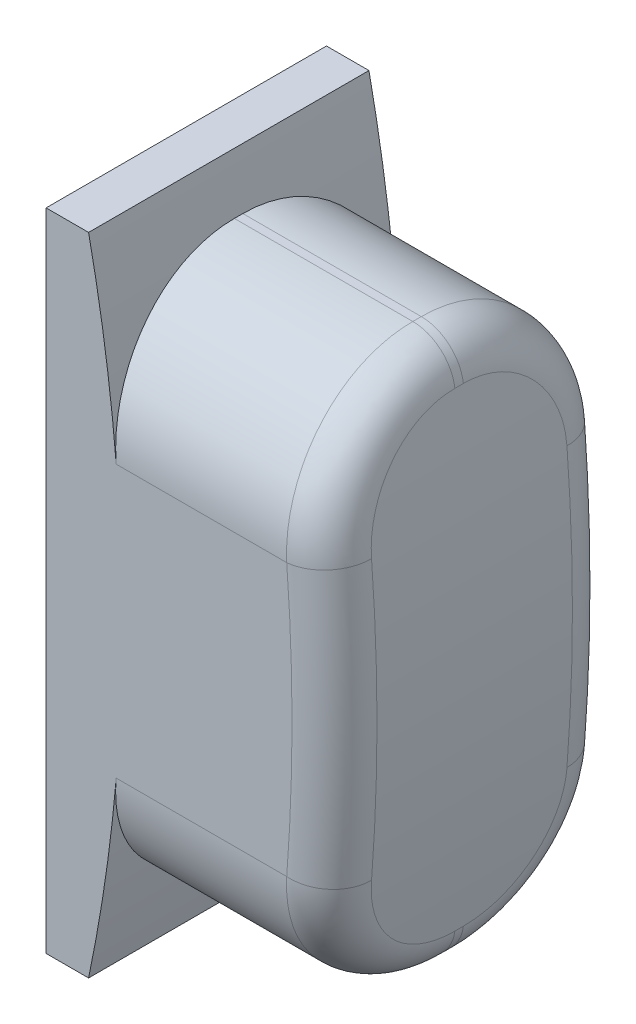
SolidWorks part; units mm, degrees
ref_plane "Ebene vorne" through (0, 0, 0) normal (0, 0, 1) x (1, 0, 0)
ref_plane "Ebene oben" through (0, 0, 0) normal (0, 1, 0) x (1, 0, 0)
ref_plane "Ebene rechts" through (0, 0, 0) normal (1, 0, 0) x (0, 0, -1)
sketch "Sketch1" plane through (0, 0, 0) normal (0, 0, 1) x (1, 0, 0)
  line L0 (0, 0) -> (21, 0) construction
  line L1 (18.2211, 3.2) -> (20.7548, 3.2)
  line L2 (18.2211, -3.2) -> (20.7548, -3.2)
  line L3 (17.6055, 3.8) -> (18.1055, 3.8)
  line L4 (17.6055, -3.8) -> (18.1055, -3.8)
  line L5 (17.6055, -3.8) -> (17.6055, 3.8)
  arc A0 (18.1055, -3.8) -> (18.2211, -3.2) centre (0, 0) ccw
  arc A1 (20.7548, -3.2) -> (20.7548, 3.2) centre (0, 0) ccw
  arc A2 (18.2211, 3.2) -> (18.1055, 3.8) centre (0, 0) ccw
  dimension "D1" = 37
  dimension "D2" = 2.5
  dimension "D3" = 3.2
  dimension "D4" = 0.6
  dimension "D5" = 0.5
extrude "Boss-Extrude1" add sketch "Sketch1" along normal mid plane 3.3
fillet "Fillet1" radius 1.6 4 edges at (19.488, -3.2, 1.65) (19.488, -3.2, -1.65) (19.488, 3.2, -1.65) (19.488, 3.2, 1.65)
fillet "Fillet2" radius 0.5 8 edges at (20.805, 2.8555, 1.0418) (20.7548, 3.2, 0) (20.8382, 2.6018, -1.2976) (21, 0, -1.65) (20.805, -2.8555, -1.0418) (20.7548, -3.2, 0) (20.8382, -2.6018, 1.2976) (21, 0, 1.65)
